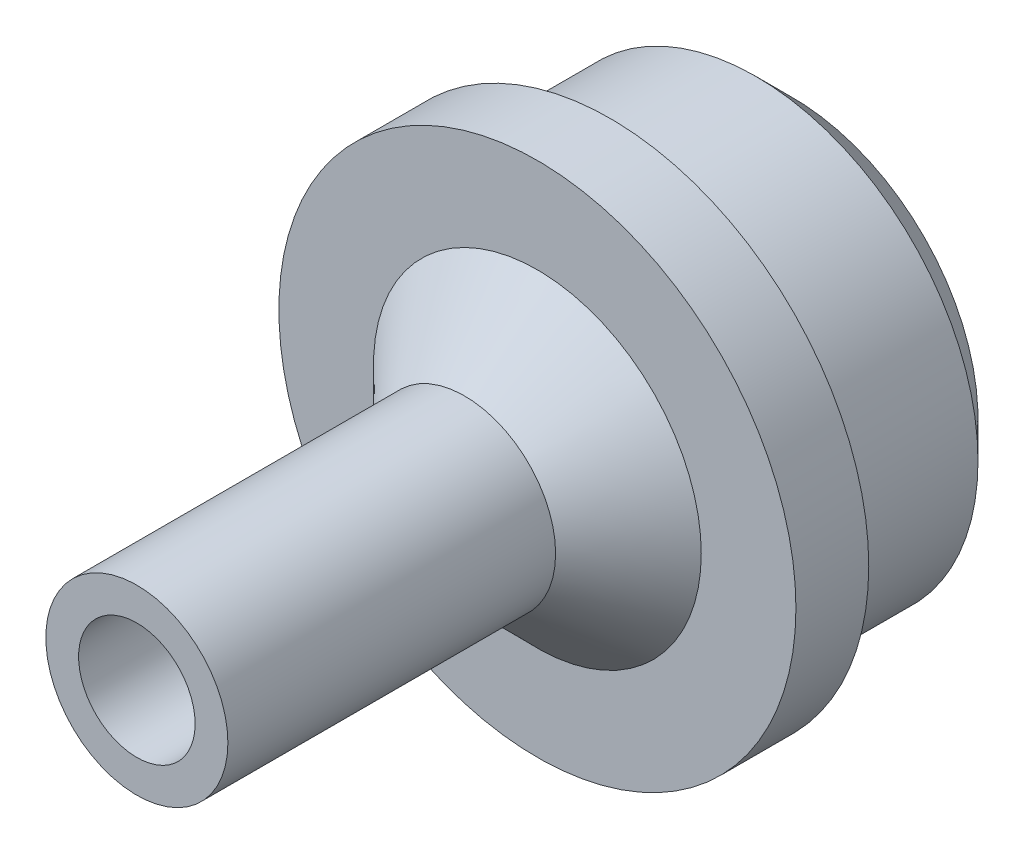
SolidWorks part; units mm, degrees
ref_plane "正面" through (0, 0, 0) normal (0, 0, 1) x (1, 0, 0)
ref_plane "平面" through (0, 0, 0) normal (0, 1, 0) x (1, 0, 0)
ref_plane "右側面" through (0, 0, 0) normal (1, 0, 0) x (0, 0, -1)
sketch "ｽｹｯﾁ1" plane through (0, 0, 0) normal (0, 0, 1) x (1, 0, 0)
  line L3 (-6.0369, 0.875) -> (-6.35, 0.875)
  line L4 (-6.35, -0.875) -> (-6.0369, -0.875)
  line L5 (-6.35, 0.875) -> (-6.35, -0.875)
  line L6 (-6.0369, 0.875) -> (-6.35, 0.875)
  line L7 (-6.35, -0.875) -> (-6.0369, -0.875)
  line L8 (-6.35, 0.875) -> (-6.35, -0.875)
  circle A1 centre (0, 0) radius 7.1
  circle A2 centre (0, 0) radius 7.1
  arc A3 (-6.0369, -0.875) -> (-6.0369, 0.875) centre (0, 0) ccw
  arc A4 (-6.0369, -0.875) -> (-6.0369, 0.875) centre (0, 0) ccw
  dimension "D1" = 0
  dimension "D2" = 0
extrude "ﾎﾞｽ - 押し出し1" add sketch "ｽｹｯﾁ1" against normal blind 5 contours L7 A4 L6 L8
sketch "ｽｹｯﾁ2" plane through (0, 0, 0) normal (0, 0, 1) x (1, 0, 0)
  circle A1 centre (0, 0) radius 7.1
  circle A2 centre (0, 0) radius 7.1
  dimension "D1" = 0
extrude "ﾎﾞｽ - 押し出し2" add sketch "ｽｹｯﾁ2" along normal blind 2
sketch "ｽｹｯﾁ3" plane through (0, 0, 2) normal (0, 0, 1) x (1, 0, 0)
  circle A0 centre (0, 0) radius 2.5
  dimension "D1" = 5
extrude "ﾎﾞｽ - 押し出し3" add sketch "ｽｹｯﾁ3" along normal blind 7
chamfer "面取り1" distance 2 angle 45 1 edges at (2.5, 0, 2)
sketch "ｽｹｯﾁ4" plane through (0, 0, 9) normal (0, 0, 1) x (1, 0, 0)
  circle A0 centre (0, 0) radius 1.6
  dimension "D1" = 3.2
extrude "ｶｯﾄ - 押し出し1" cut sketch "ｽｹｯﾁ4" against normal blind 30
chamfer "面取り2" distance 1 angle 45 1 edges at (6.1, 0, -5)
other "面の移動1" face at (1.6, 0, 9) parameters "D1"=4
